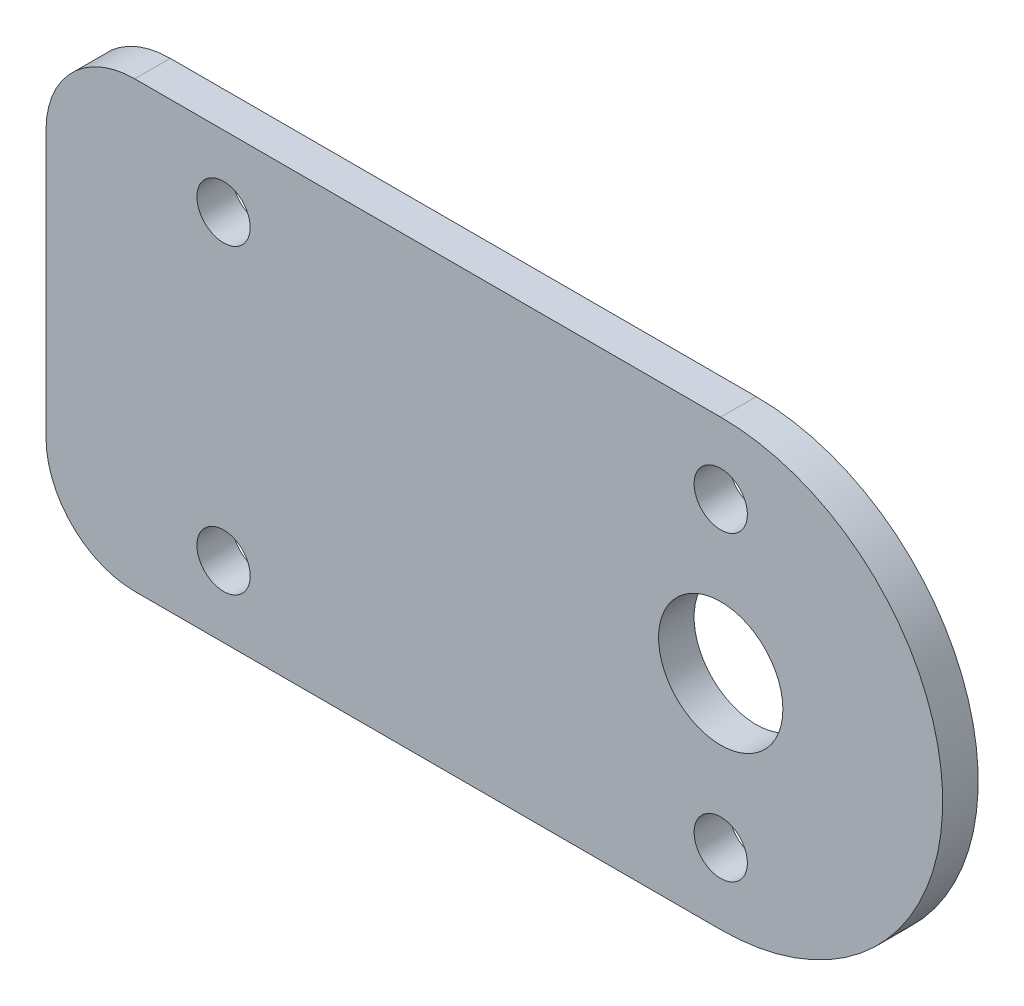
SolidWorks part; units mm, degrees
ref_plane "前视基准面" through (0, 0, 0) normal (0, 0, 1) x (1, 0, 0)
ref_plane "上视基准面" through (0, 0, 0) normal (0, 1, 0) x (1, 0, 0)
ref_plane "右视基准面" through (0, 0, 0) normal (1, 0, 0) x (0, 0, -1)
other "Configuration Table"
sketch "草图1" plane through (0, 0, 0) normal (0, 0, 1) x (1, 0, 0)
  line L0 (11.1923, 0) -> (21.8684, 0) construction
  line L1 (21.5, -12.5) -> (-16.5, -12.5)
  line L3 (21.5, 12.5) -> (-16.5, 12.5)
  line L4 (-16.5, -12.5) -> (-16.5, 12.5)
  line L5 (-16.5, 0) -> (2.3076, 0) construction
  arc A0 (21.5, 12.5) -> (21.5, -12.5) centre (21.5, 0) cw
  circle A1 centre (21.5, 0) radius 3.5
  circle A3 centre (21.5, 8.5) radius 1.5
  circle A4 centre (21.5, -8.5) radius 1.5
  circle A5 centre (-6.5, 8.5) radius 1.5
  circle A6 centre (-6.5, -8.5) radius 1.5
  point P0 (0, 0)
  dimension "D3" = 7
  dimension "D4" = 3
  dimension "D5" = 3
  dimension "D1" = 38
  dimension "D2" = 25
  dimension "D6" = 8.5
  dimension "D7" = 10
  dimension "D8" = 28
extrude "凸台-拉伸1" add sketch "草图1" along normal blind 2
fillet "圆角1" radius 5 2 edges at (-16.5, -12.5, 1) (-16.5, 12.5, 1)
